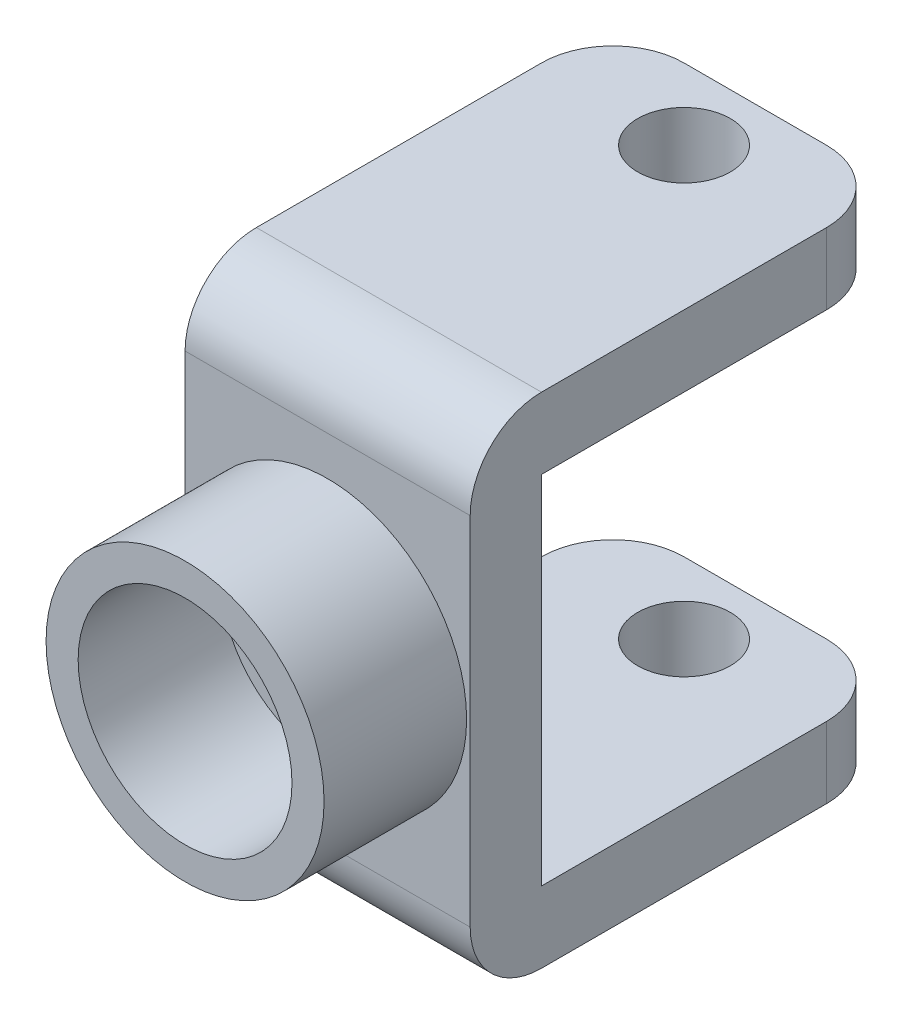
SolidWorks part; units mm, degrees
material "Alloy Steel"
ref_plane "Front Plane" through (0, 0, 0) normal (0, 0, 1) x (1, 0, 0)
ref_plane "Top Plane" through (0, 0, 0) normal (0, 1, 0) x (1, 0, 0)
ref_plane "Right Plane" through (0, 0, 0) normal (1, 0, 0) x (0, 0, -1)
sketch "Sketch1" plane through (0, 0, 0) normal (0, 0, 1) x (1, 0, 0)
  line L1 (-20, -25) -> (20, -25)
  line L2 (-20, -25) -> (-20, 25)
  line L3 (-20, 25) -> (20, 25)
  line L4 (20, -25) -> (20, 25)
  line L5 (-20, -25) -> (20, 25) construction
  line L6 (-20, 25) -> (20, -25) construction
  point P0 (0, 0)
  dimension "D1" = 40
  dimension "D2" = 50
extrude "Boss-Extrude1" add sketch "Sketch1" along normal blind 10 contours L1 L4 L3 L2
sketch "Sketch3" plane through (0, 0, 0) normal (1, 0, 0) x (0, 0, -1)
  line L0 (-10, -25) -> (-10, 25) construction
  line L1 (-10, -25) -> (50, -25)
  line L2 (-10, -25) -> (-10, -35)
  line L3 (-10, -35) -> (50, -35)
  line L4 (50, -25) -> (50, -35)
  line L5 (-10, -25) -> (0, -25) construction
  line L6 (-10, 25) -> (0, 25) construction
  line L7 (-10, 25) -> (50, 25)
  line L8 (-10, 25) -> (-10, 35)
  line L9 (-10, 35) -> (50, 35)
  line L10 (50, 25) -> (50, 35)
  dimension "D1" = 10
  dimension "D2" = 10
  dimension "D3" = 60
  dimension "D4" = 60
extrude "Boss-Extrude2" add sketch "Sketch3" along normal mid plane 40
fillet "Fillet1" radius 10 6 edges at (0, 35, 10) (0, -35, 10) (-20, -30, -50) (20, -30, -50) (-20, 30, -50) (20, 30, -50)
sketch "Sketch4" plane through (0, 0, 10) normal (0, 0, 1) x (1, 0, 0)
  circle A0 centre (0, 0) radius 19.5
  circle A1 centre (0, 0) radius 15
  dimension "D1" = 30
  dimension "D2" = 39
extrude "Boss-Extrude3" add sketch "Sketch4" along normal blind 20
sketch "Sketch5" plane through (0, -35, 0) normal (0, -1, 0) x (1, 0, 0)
  line L0 (0, -50) -> (0, -40) construction
  line L1 (10, -50) -> (-10, -50) construction
  circle A0 centre (0, -40) radius 6.5
  dimension "D2" = 13
  dimension "D1" = 10
extrude "Cut-Extrude1" cut sketch "Sketch5" against normal blind 100
